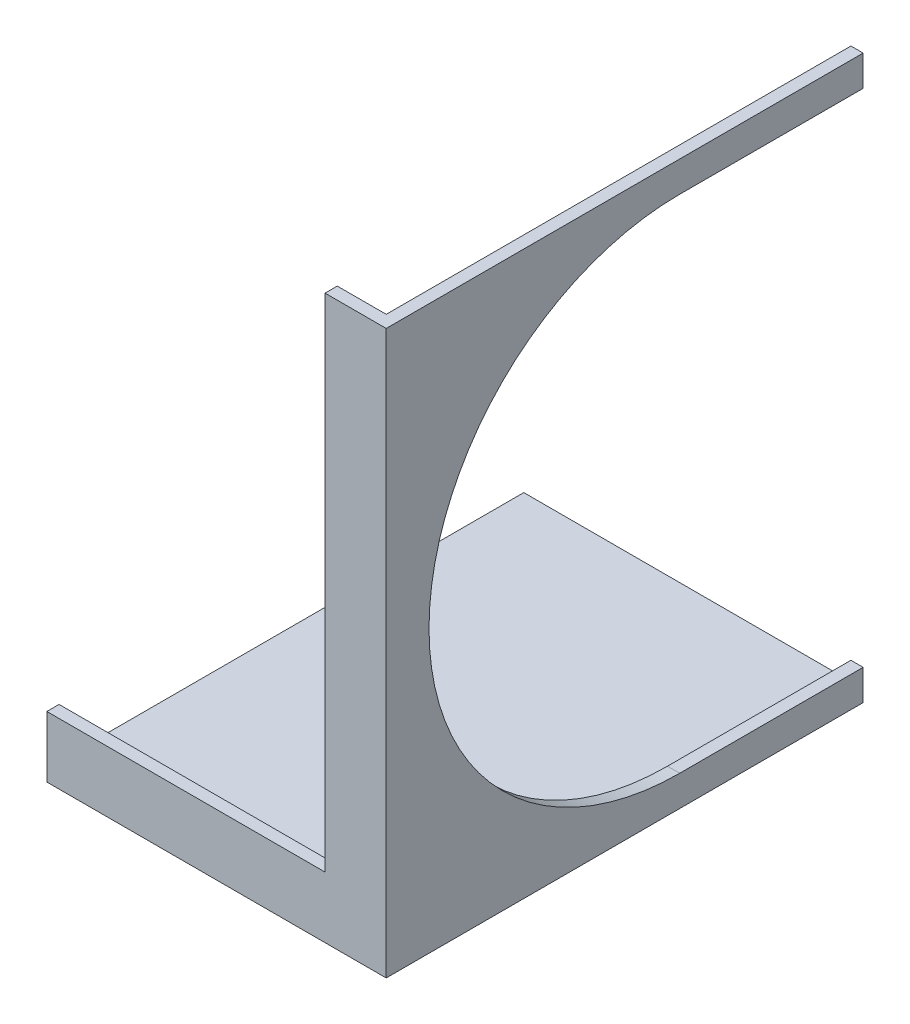
SolidWorks part; units mm, degrees
ref_plane "前视基准面" through (0, 0, 0) normal (0, 0, 1) x (1, 0, 0)
ref_plane "上视基准面" through (0, 0, 0) normal (0, 1, 0) x (1, 0, 0)
ref_plane "右视基准面" through (0, 0, 0) normal (1, 0, 0) x (0, 0, -1)
sketch "草图1" plane through (0, 0, 0) normal (0, 0, 1) x (1, 0, 0)
  line L0 (-55.5, 0) -> (0, 0)
  line L1 (0, 0) -> (0, 92)
  line L2 (0, 92) -> (-2, 92)
  line L3 (-2, 92) -> (-2, 2)
  line L4 (-2, 2) -> (-55.5, 2)
  line L5 (-55.5, 2) -> (-55.5, 0)
  dimension "D1" = 2
  dimension "D2" = 2
  dimension "D3" = 55.5
  dimension "D4" = 92
extrude "凸台-拉伸1" add sketch "草图1" along normal blind 76
sketch "草图2" plane through (0, 0, 0) normal (1, 0, 0) x (0, 0, -1)
  line L0 (0, 0) -> (0, 92) construction
  line L2 (-76, 0) -> (-76, 92) construction
  line L3 (-30, 5) -> (0, 5)
  line L4 (-30, 87) -> (0, 87)
  line L5 (0, 87) -> (0, 5)
  line L6 (0, 46) -> (-37.3505, 46) construction
  arc A0 (-30, 87) -> (-30, 5) centre (-30, 46) ccw
  dimension "D2" = 41
  dimension "D1" = 46
extrude "切除-拉伸1" cut sketch "草图2" against normal blind 70
sketch "草图3" plane through (0, 0, 76) normal (0, 0, 1) x (1, 0, 0)
  line L0 (0, 92) -> (-10, 92)
  line L1 (-10, 92) -> (-10, 10)
  line L2 (-10, 10) -> (-55.5, 10)
  line L3 (-55.5, 10) -> (-55.5, 0)
  line L4 (-55.5, 0) -> (0, 0)
  line L5 (0, 0) -> (0, 92)
  dimension "D1" = 10
  dimension "D2" = 10
extrude "凸台-拉伸2" add sketch "草图3" along normal blind 2
